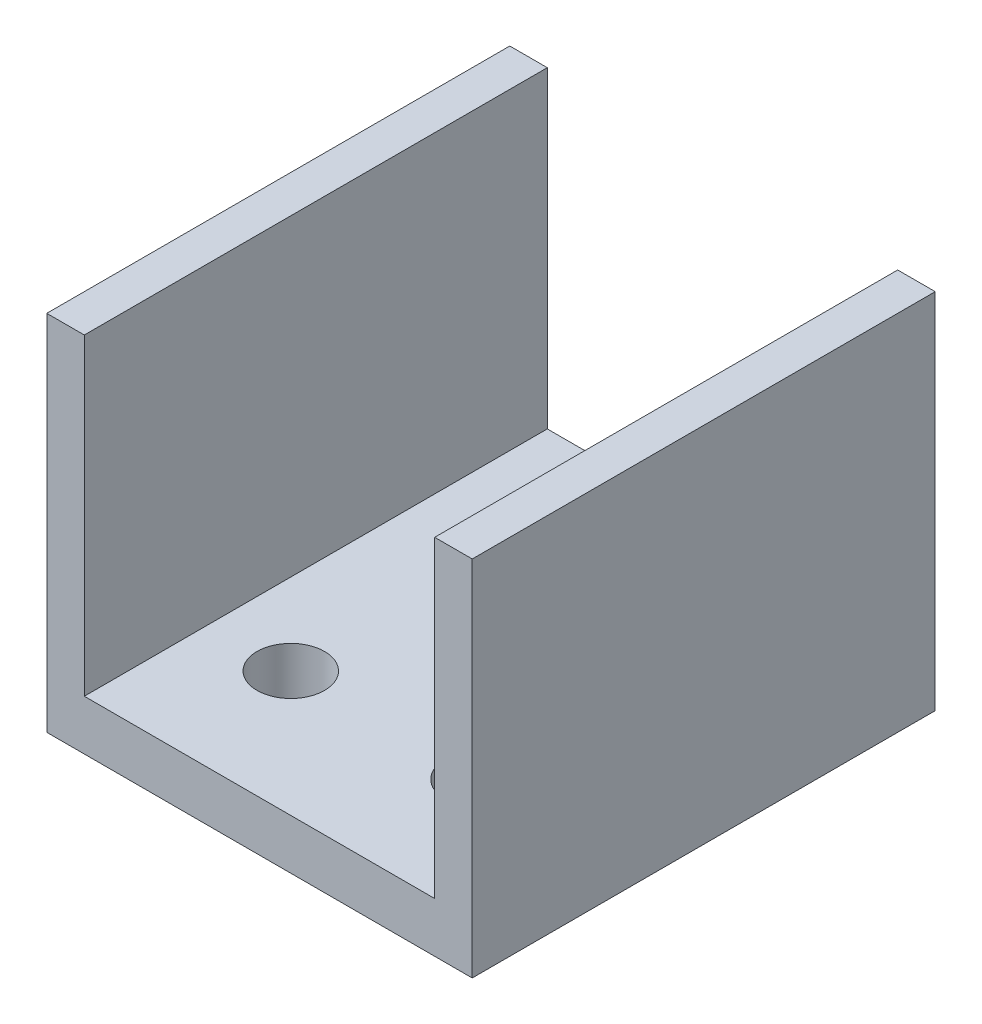
SolidWorks part; units mm, degrees
ref_plane "Front Plane" through (0, 0, 0) normal (0, 0, 1) x (1, 0, 0)
ref_plane "Top Plane" through (0, 0, 0) normal (0, 1, 0) x (1, 0, 0)
ref_plane "Right Plane" through (0, 0, 0) normal (1, 0, 0) x (0, 0, -1)
sketch "Sketch1" plane through (0, 0, 0) normal (0, 1, 0) x (1, 0, 0)
  line L0 (-18.8254, 27.9242) -> (-18.8254, -9.0758) construction
  line L1 (-35.8254, -9.0758) -> (-1.8254, -9.0758)
  line L2 (-35.8254, -9.0758) -> (-35.8254, 27.9242)
  line L3 (-35.8254, 27.9242) -> (-1.8254, 27.9242)
  line L4 (-1.8254, -9.0758) -> (-1.8254, 27.9242)
  circle A0 centre (-18.8254, 20.9242) radius 2.7
  circle A2 centre (-11.3254, 0.9242) radius 2.7
  circle A3 centre (-26.3254, 0.9242) radius 2.7
  dimension "D3" = 7
  dimension "D4" = 10
  dimension "D6" = 5.4
  dimension "D1" = 37
  dimension "D2" = 34
  dimension "D5" = 7.5
extrude "Boss-Extrude1" add sketch "Sketch1" along normal blind 4
sketch "Sketch7" [suppressed] plane through (0, 0, 41.8258) normal (0, 0, 1) x (1, 0, 0)
  line L0 (-35.8254, 32.925) -> (8.1746, 32.925) construction
  line L3 (-35.8254, 25) -> (-35.8254, 38) construction
  line L4 (-0.8254, 25) -> (-0.8254, 38) construction
  circle A0 centre (-4.8254, 32.925) radius 1.45
  circle A1 centre (-31.8254, 32.925) radius 1.45
  dimension "D1" = 4
  dimension "D2" = 4
  dimension "D3" = 2.9
  dimension "D4" = 2.9
extrude "Cut-Extrude1" [suppressed] cut sketch "Sketch7" against normal blind 5
sketch "Sketch30" plane through (-35.8254, 0, 0) normal (-1, 0, 0) x (0, 0, 1)
  line L1 (9.0758, 4) -> (-27.9242, 4)
  line L2 (9.0758, 4) -> (9.0758, 29)
  line L3 (9.0758, 29) -> (-27.9242, 29)
  line L4 (-27.9242, 4) -> (-27.9242, 29)
  dimension "D1" = 25
extrude "Boss-Extrude19" add sketch "Sketch30" against normal blind 3
sketch "Sketch31" plane through (-1.8254, 0, 0) normal (1, 0, 0) x (0, 0, -1)
  line L5 (27.9242, 4) -> (-9.0758, 4)
  line L6 (27.9242, 4) -> (27.9242, 29)
  line L7 (27.9242, 29) -> (-9.0758, 29)
  line L8 (-9.0758, 4) -> (-9.0758, 29)
extrude "Boss-Extrude20" add sketch "Sketch31" against normal blind 3
sketch "Sketch32" plane through (-35.8254, 0, 0) normal (-1, 0, 0) x (0, 0, 1)
  line L0 (9.0758, 25) -> (-27.9242, 25) construction
  line L1 (9.0758, 29) -> (9.0758, 0) construction
  line L2 (-27.9242, 29) -> (-27.9242, 0) construction
  line L3 (9.0758, 29) -> (-27.9242, 29) construction
  circle A0 centre (3.0758, 25) radius 1.4
  circle A2 centre (-16.9242, 25) radius 1.4
  circle A3 centre (-6.9242, 25) radius 1.4 [skipped]
  dimension "D1" = 2.8
  dimension "D2" = 6
  dimension "D4" = 4
  dimension "D3" = 3
extrude "Cut-Extrude2" [suppressed] cut sketch "Sketch32" against normal through all both and the other way through all
chamfer "Chamfer22" [suppressed] distance 12 angle 30
